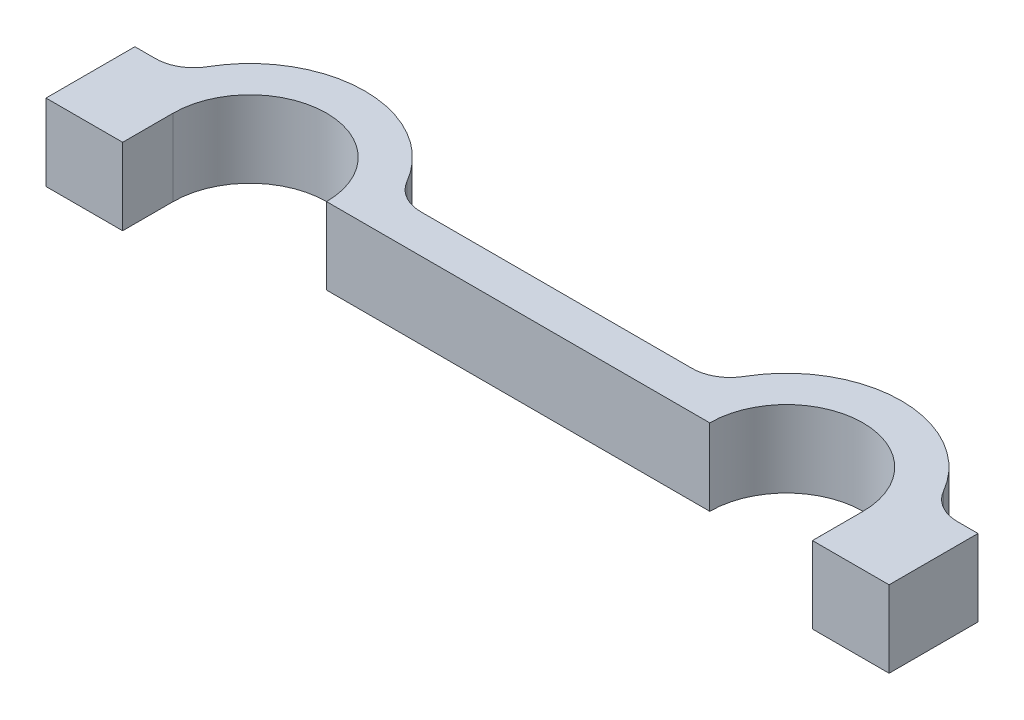
SolidWorks part; units mm, degrees
ref_plane "Front Plane" through (0, 0, 0) normal (0, 0, 1) x (1, 0, 0)
ref_plane "Top Plane" through (0, 0, 0) normal (0, 1, 0) x (1, 0, 0)
ref_plane "Right Plane" through (0, 0, 0) normal (1, 0, 0) x (0, 0, -1)
sketch "Sketch1" plane through (0, 0, 0) normal (0, 1, 0) x (1, 0, 0)
  line L0 (25.4, 0) -> (88.9, 0)
  line L1 (114.3, 0) -> (127, 0)
  line L2 (0, 0) -> (-12.7, 0)
  line L3 (123.597, 6.35) -> (127, 6.35)
  line L4 (34.697, 6.35) -> (79.603, 6.35)
  line L5 (-9.297, 6.35) -> (-12.7, 6.35)
  line L6 (-12.7, 0) -> (-12.7, 6.35)
  line L7 (127, 0) -> (127, 6.35)
  line L8 (119.5605, 6.35) -> (127, 6.35) construction
  line L9 (30.6605, 6.35) -> (83.6395, 6.35) construction
  line L10 (-5.2605, 6.35) -> (-12.7, 6.35) construction
  arc A0 (0, 0) -> (25.4, 0) centre (12.7, 0) cw
  arc A1 (88.9, 0) -> (114.3, 0) centre (101.6, 0) cw
  arc A2 (85.1022, 9.525) -> (118.0978, 9.525) centre (101.6, 0) cw
  arc A3 (-3.7978, 9.525) -> (29.1978, 9.525) centre (12.7, 0) cw
  arc A4 (83.6395, 6.35) -> (119.5605, 6.35) centre (101.6, 0) cw construction
  arc A5 (123.597, 6.35) -> (118.0978, 9.525) centre (123.597, 12.7) cw
  arc A6 (85.1022, 9.525) -> (79.603, 6.35) centre (79.603, 12.7) cw
  arc A7 (-5.2605, 6.35) -> (30.6605, 6.35) centre (12.7, 0) cw construction
  arc A8 (34.697, 6.35) -> (29.1978, 9.525) centre (34.697, 12.7) cw
  arc A9 (-3.7978, 9.525) -> (-9.297, 6.35) centre (-9.297, 12.7) cw
  dimension "D1" = 12.7
  dimension "D6" = 6.35
  dimension "D2" = 88.9
  dimension "D4" = 12.7
  dimension "D5" = 12.7
  dimension "D3" = 6.35
extrude "Boss-Extrude1" add sketch "Sketch1" along normal blind 12.7
sketch "Sketch2" plane through (0, 0, 0) normal (0, 0, 1) x (1, 0, 0)
  line L1 (-12.7, 0) -> (0, 0)
  line L2 (-12.7, 0) -> (-12.7, 12.7)
  line L3 (-12.7, 12.7) -> (0, 12.7)
  line L4 (0, 0) -> (0, 12.7)
  line L5 (114.3, 0) -> (127, 0)
  line L6 (114.3, 0) -> (114.3, 12.7)
  line L7 (114.3, 12.7) -> (127, 12.7)
  line L8 (127, 0) -> (127, 12.7)
extrude "Boss-Extrude2" add sketch "Sketch2" along normal blind 8.382
